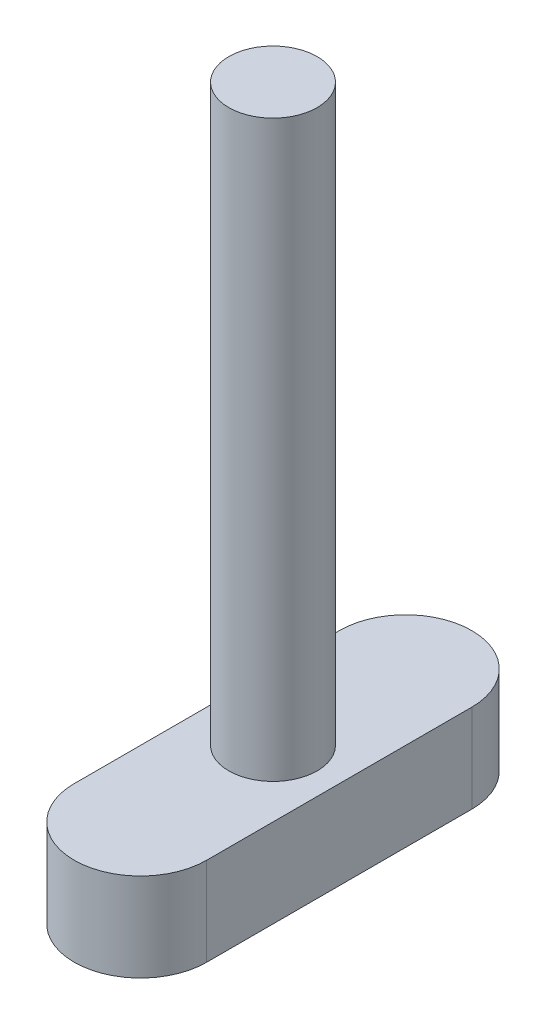
SolidWorks part; units mm, degrees
ref_plane "Front Plane" through (0, 0, 0) normal (0, 0, 1) x (1, 0, 0)
ref_plane "Top Plane" through (0, 0, 0) normal (0, 1, 0) x (1, 0, 0)
ref_plane "Right Plane" through (0, 0, 0) normal (1, 0, 0) x (0, 0, -1)
sketch "Sketch1" plane through (0, 0, 0) normal (0, 1, 0) x (1, 0, 0)
  line L0 (-43.2744, 0) -> (43.2744, 0) construction
  line L1 (0, 15) -> (0, -15) construction
  line L2 (-7.5, -15) -> (-7.5, 15)
  line L3 (7.5, 15) -> (7.5, -15)
  arc A0 (7.5, 15) -> (-7.5, 15) centre (0, 15) ccw
  arc A1 (7.5, -15) -> (-7.5, -15) centre (0, -15) cw
  point P4 (0, 0)
  point P8 (0, 0)
  point P14 (7.5, 0)
  point P15 (-7.5, 0)
  point P16 (0, 0)
  dimension "D1" = 15
  dimension "D2" = 15
extrude "Boss-Extrude1" add sketch "Sketch1" along normal blind 10
sketch "Sketch2" plane through (0, 10, 0) normal (0, 1, 0) x (1, 0, 0)
  circle A0 centre (0, 0) radius 5
extrude "Boss-Extrude2" add sketch "Sketch2" along normal blind 65 contours A0
